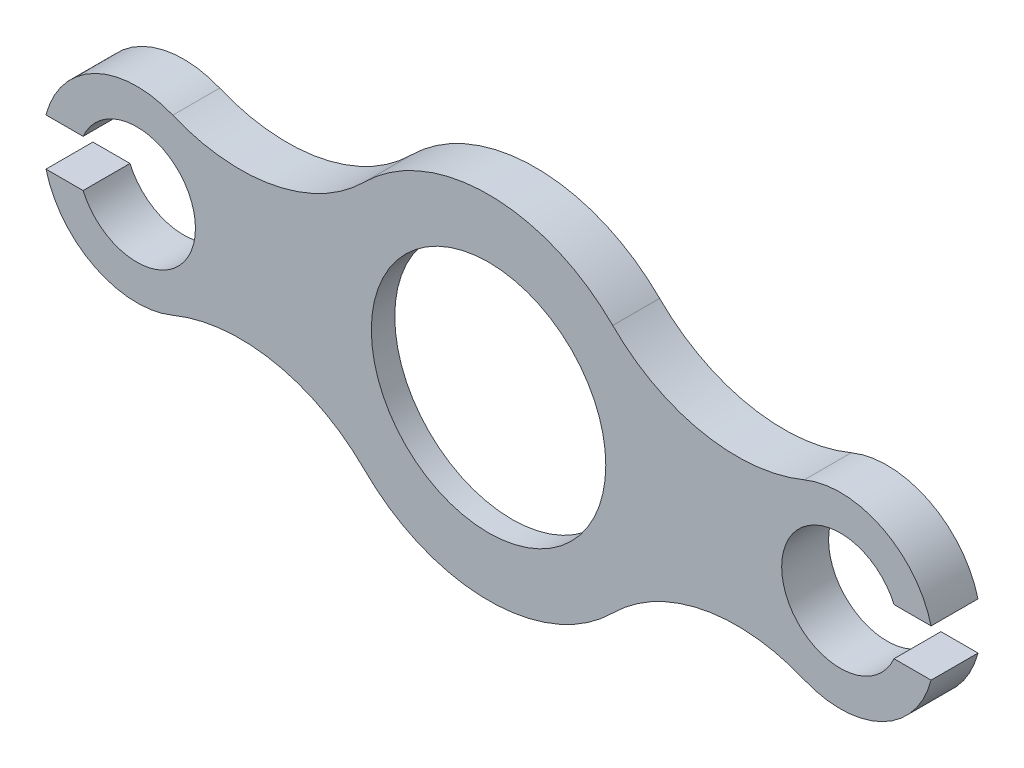
SolidWorks part; units mm, degrees
material "AISI 1020"
ref_plane "Plan de face" through (0, 0, 0) normal (0, 0, 1) x (1, 0, 0)
ref_plane "Plan de dessus" through (0, 0, 0) normal (0, 1, 0) x (1, 0, 0)
ref_plane "Plan de droite" through (0, 0, 0) normal (1, 0, 0) x (0, 0, -1)
sketch "Esquisse1" plane through (0, 0, 0) normal (0, 0, 1) x (1, 0, 0)
  line L0 (102.3708, 0) -> (75, 0) construction
  line L1 (68.25, 0) -> (-68.25, 0) construction
  line L5 (0, 0) -> (0, 110.8105)
  line L9 (-172.9129, 10) -> (-188.7298, 10)
  line L10 (-172.9129, -10) -> (-188.7298, -10)
  line L11 (172.9129, -10) -> (188.7298, -10)
  line L12 (172.9129, 10) -> (188.7298, 10)
  line L13 (-75, 0) -> (-102.3708, 0) construction
  arc A0 (-74.3303, 10) -> (-74.3303, -10) centre (0, 0) ccw
  circle A1 centre (0, 0) radius 50
  arc A3 (-188.7298, -10) -> (-134.6667, -36.9444) centre (-150, 0) ccw
  arc A4 (-172.9129, -10) -> (-172.9129, 10) centre (-150, 0) ccw
  arc A5 (-134.6667, 36.9444) -> (-52.9583, 53.1076) centre (-105.9167, 106.2152) ccw
  arc A6 (-134.6667, -36.9444) -> (-52.9583, -53.1076) centre (-105.9167, -106.2152) cw
  arc A7 (-134.6667, 36.9444) -> (-188.7298, 10) centre (-150, 0) ccw
  arc A8 (134.6667, 36.9444) -> (188.7298, 10) centre (150, 0) cw
  arc A9 (134.6667, -36.9444) -> (52.9583, -53.1076) centre (105.9167, -106.2152) ccw
  arc A10 (134.6667, 36.9444) -> (52.9583, 53.1076) centre (105.9167, 106.2152) cw
  arc A11 (172.9129, -10) -> (172.9129, 10) centre (150, 0) cw
  arc A12 (188.7298, -10) -> (134.6667, -36.9444) centre (150, 0) cw
  arc A13 (-52.9583, -53.1076) -> (-52.9583, 53.1076) centre (0, 0) ccw
  circle A14 centre (0, 0) radius 68.25
  dimension "D1" = 75
  dimension "D2" = 100
  dimension "D3" = 136.5
  dimension "D4" = 40
  dimension "D5" = 50
  dimension "D8" = 75
  dimension "D6" = 150
  dimension "D7" = 20
extrude "Boss.-Extru.3" add sketch "Esquisse1" along normal blind 20
sketch "Esquisse2" plane through (0, 0, 0) normal (0, 0, 1) x (1, 0, 0)
  circle A0 centre (0, 0) radius 68.25
  dimension "D1" = 136.5
extrude "Enlèv. mat.-Extru.9" cut sketch "Esquisse2" along normal blind 10
